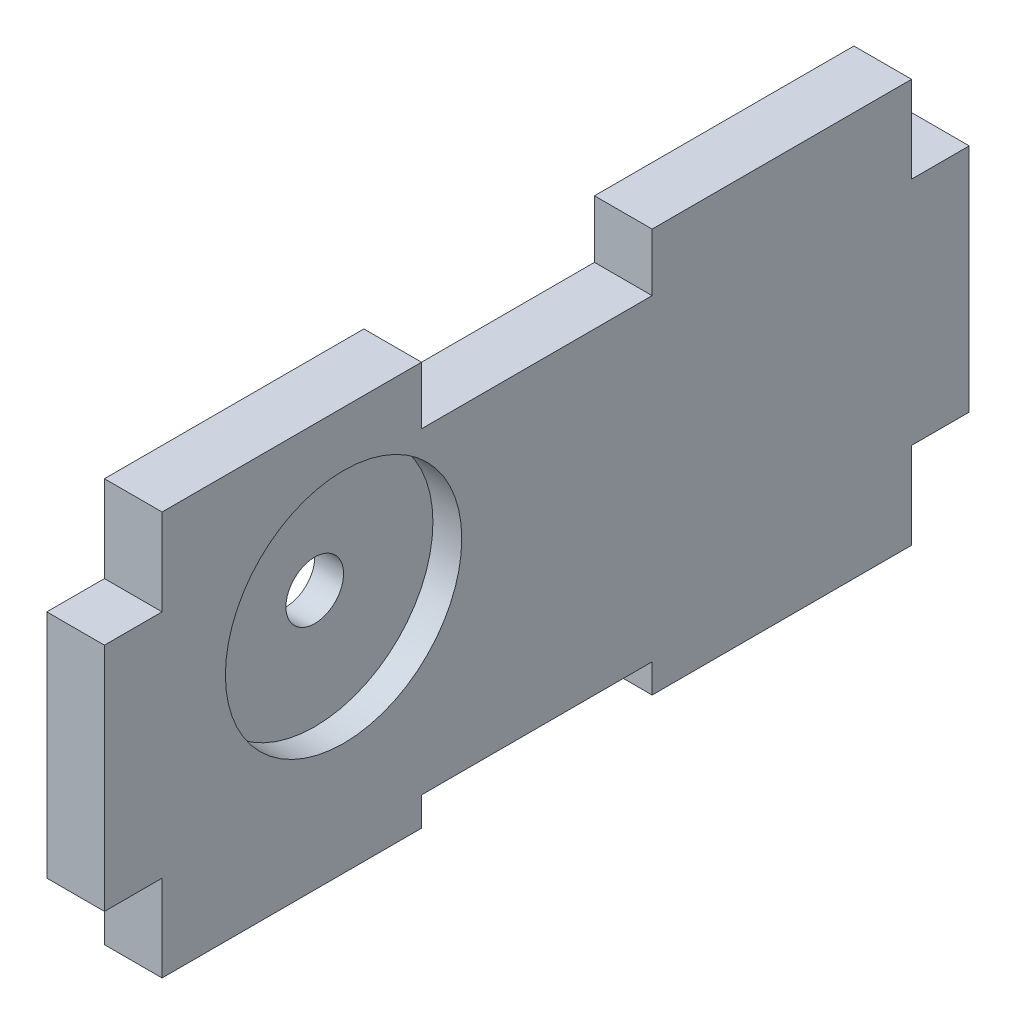
SolidWorks part; units mm, degrees
ref_plane "Front Plane" through (0, 0, 0) normal (0, 0, 1) x (1, 0, 0)
ref_plane "Top Plane" through (0, 0, 0) normal (0, 1, 0) x (1, 0, 0)
ref_plane "Right Plane" through (0, 0, 0) normal (1, 0, 0) x (0, 0, -1)
sketch "Sketch1" plane through (0, 0, 0) normal (1, 0, 0) x (0, 0, -1)
  line L1 (-150, 70) -> (0, 70)
  line L2 (-150, 70) -> (-150, 0)
  line L3 (-150, 0) -> (0, 0)
  line L4 (0, 70) -> (0, 0)
  line L5 (-150, 70) -> (-140, 70)
  line L6 (-150, 70) -> (-150, 55)
  line L7 (-150, 55) -> (-140, 55)
  line L8 (-140, 70) -> (-140, 55)
  line L9 (-150, 0) -> (-140, 0)
  line L10 (-150, 0) -> (-150, 15)
  line L11 (-150, 15) -> (-140, 15)
  line L12 (-140, 0) -> (-140, 15)
  line L13 (0, 70) -> (-10, 70)
  line L14 (0, 70) -> (0, 55)
  line L15 (0, 55) -> (-10, 55)
  line L16 (-10, 70) -> (-10, 55)
  line L17 (0, 0) -> (-10, 0)
  line L18 (0, 0) -> (0, 15)
  line L19 (0, 15) -> (-10, 15)
  line L20 (-10, 0) -> (-10, 15)
  line L21 (-95, 70) -> (-55, 70)
  line L22 (-95, 70) -> (-95, 60)
  line L23 (-95, 60) -> (-55, 60)
  line L24 (-55, 70) -> (-55, 60)
  line L25 (-95, 0) -> (-55, 0)
  line L26 (-95, 0) -> (-95, 5)
  line L27 (-95, 5) -> (-55, 5)
  line L28 (-55, 0) -> (-55, 5)
  dimension "D1" = 150
  dimension "D2" = 70
  dimension "D3" = 10
  dimension "D4" = 15
  dimension "D5" = 10
  dimension "D6" = 15
  dimension "D7" = 15
  dimension "D8" = 10
  dimension "D9" = 10
  dimension "D10" = 15
  dimension "D11" = 10
  dimension "D12" = 40
  dimension "D13" = 55
  dimension "D14" = 55
  dimension "D15" = 40
  dimension "D16" = 5
extrude "Boss-Extrude1" add sketch "Sketch1" along normal blind 10 contours L28 L3 L20 L19 L4 L15 L16 L1 L24 L23 L22 L8 L7 L2 L11 L12 L26 L27
sketch "Sketch2" plane through (10, 0, 0) normal (1, 0, 0) x (0, 0, -1)
  line L1 (-150, 55) -> (-150, 15) construction
  line L2 (-95, 5) -> (-55, 5) construction
  circle A0 centre (-108.52, 40) radius 20.5
  dimension "D3" = 41
  dimension "D1" = 35
  dimension "D2" = 41.48
extrude "Cut-Extrude1" cut sketch "Sketch2" against normal blind 5 contours A0
sketch "Sketch4" plane through (5, 0, 0) normal (1, 0, 0) x (0, 0, -1)
  circle A0 centre (-108.52, 40) radius 5
  dimension "D1" = 10
extrude "Cut-Extrude3" cut sketch "Sketch4" against normal through all
sketch "Sketch5" plane through (0, 0, 0) normal (-1, 0, 0) x (0, 0, 1)
  line L0 (95, 5) -> (55, 5) construction
  line L1 (55, 5) -> (10, 5)
  line L2 (10, 0) -> (10, 15) construction
  line L3 (140, 70) -> (140, 55) construction
  circle A0 centre (72.52, 33) radius 5
  circle A1 centre (37.0801, 26.6744) radius 5
  dimension "D1" = 10
  dimension "D4" = 10
  dimension "D2" = 28
  dimension "D3" = 67.48
  dimension "D5" = 36
extrude "Cut-Extrude4" cut sketch "Sketch5" against normal blind 5 contours A1 | A0
